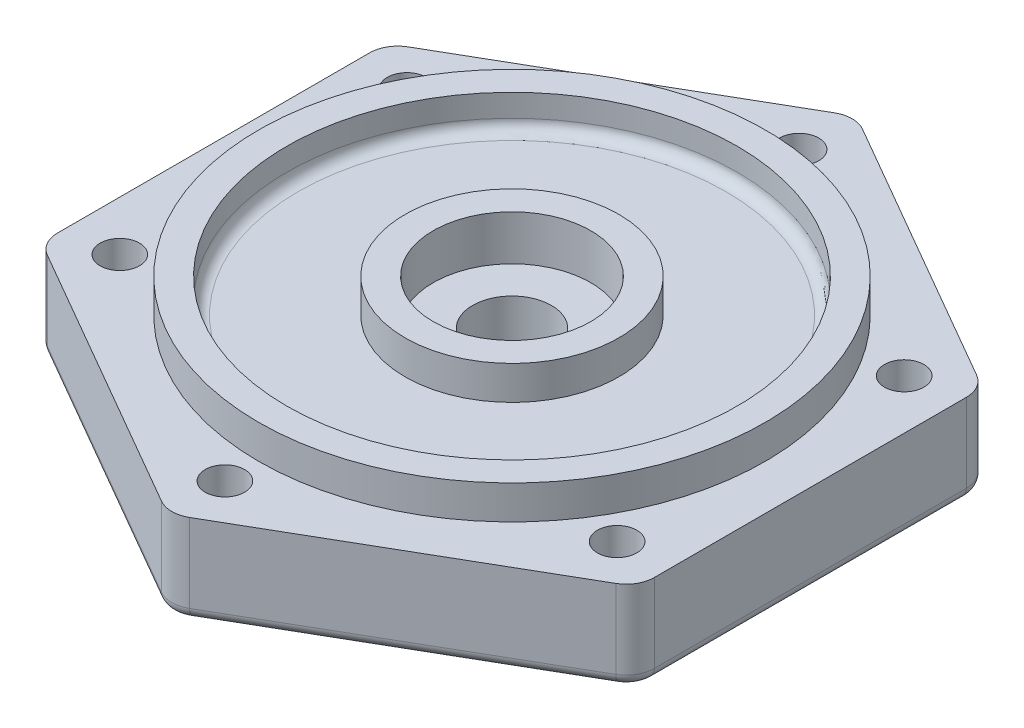
SolidWorks part; units mm, degrees
ref_plane "Front Plane" through (0, 0, 0) normal (0, 0, 1) x (1, 0, 0)
ref_plane "Top Plane" through (0, 0, 0) normal (0, 1, 0) x (1, 0, 0)
ref_plane "Right Plane" through (0, 0, 0) normal (1, 0, 0) x (0, 0, -1)
sketch "Sketch1" plane through (0, 0, 0) normal (0, 1, 0) x (1, 0, 0)
  line L1 (-2.5, 59.7558) -> (-50.5, 32.0429)
  line L2 (-53, 27.7128) -> (-53, -27.7128)
  line L3 (-50.5, -32.0429) -> (-2.5, -59.7558)
  line L4 (2.5, -59.7558) -> (50.5, -32.0429)
  line L5 (53, -27.7128) -> (53, 27.7128)
  line L6 (50.5, 32.0429) -> (2.5, 59.7558)
  circle A0 centre (0, 0) radius 53 construction
  arc A1 (50.5, -32.0429) -> (53, -27.7128) centre (48, -27.7128) ccw
  arc A2 (-2.5, -59.7558) -> (2.5, -59.7558) centre (0, -55.4256) ccw
  arc A3 (-53, -27.7128) -> (-50.5, -32.0429) centre (-48, -27.7128) ccw
  arc A4 (-50.5, 32.0429) -> (-53, 27.7128) centre (-48, 27.7128) ccw
  arc A5 (53, 27.7128) -> (50.5, 32.0429) centre (48, 27.7128) ccw
  arc A6 (-2.5, 59.7558) -> (2.5, 59.7558) centre (0, 55.4256) cw
  circle A7 centre (0, 0) radius 7
  circle A8 centre (0, 0) radius 51 construction
  circle A9 centre (0, 51) radius 3.5
  circle A10 centre (44.1673, 25.5) radius 3.5
  circle A11 centre (44.1673, -25.5) radius 3.5
  circle A12 centre (0, -51) radius 3.5
  circle A13 centre (-44.1673, -25.5) radius 3.5
  circle A14 centre (-44.1673, 25.5) radius 3.5
  point P38 (0, 0)
  dimension "D2" = 5
  dimension "D3" = 14
  dimension "D4" = 102
  dimension "D5" = 7
  dimension "D1" = 106
  dimension "D6" = 6
extrude "Boss-Extrude1" add sketch "Sketch1" along normal blind 16
sketch "Sketch2" plane through (0, 16, 0) normal (0, 1, 0) x (1, 0, 0)
  circle A0 centre (0, 0) radius 19
  circle A1 centre (0, 0) radius 40
  circle A2 centre (0, 0) radius 45
  circle M18 centre (0, 0) radius 7
  dimension "D1" = 38
  dimension "D2" = 80
  dimension "D3" = 90
extrude "Boss-Extrude2" add sketch "Sketch2" along normal blind 6 contours A2 A1 | A0 M18 | M18
sketch "Sketch3" plane through (0, 22, 0) normal (0, 1, 0) x (1, 0, 0)
  circle A0 centre (0, 0) radius 14
  dimension "D1" = 28
extrude "Cut-Extrude1" cut sketch "Sketch3" against normal blind 8
sketch "Sketch4" plane through (0, 0, 0) normal (0, -1, 0) x (1, 0, 0)
  circle A0 centre (0, 0) radius 23
  circle A1 centre (0, 0) radius 7 construction
  circle A2 centre (0, 0) radius 7
  dimension "D1" = 46
extrude "Boss-Extrude3" add sketch "Sketch4" along normal blind 4
fillet "Fillet1" radius 2 14 edges at (0, 16, 40) (0, 0, 23) (52.3301, 0, 30.2128) (26.5, 0, 45.8993) (0, 0, 60.4256) (-26.5, 0, 45.8993) (-52.3301, 0, 30.2128) (-53, 0, 0) (-52.3301, 0, -30.2128) (-26.5, 0, -45.8993) (0, 0, -60.4256) (26.5, 0, -45.8993) (52.3301, 0, -30.2128) (53, 0, 0)
